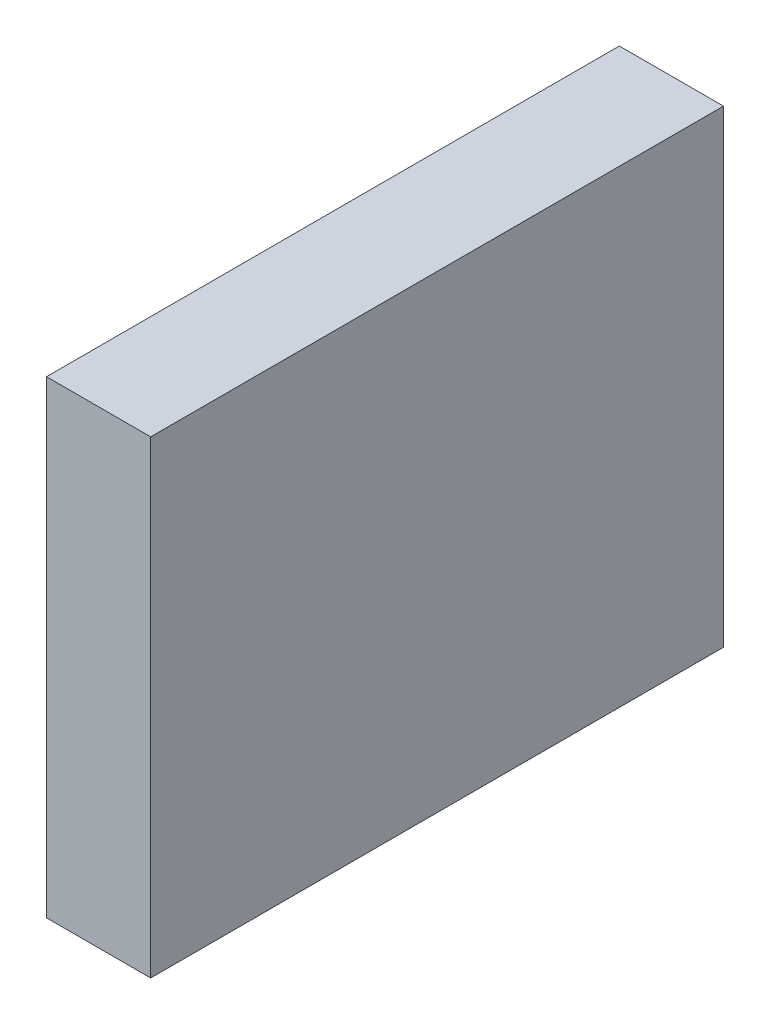
SolidWorks part; units mm, degrees
ref_plane "前视基准面" through (0, 0, 0) normal (0, 0, 1) x (1, 0, 0)
ref_plane "上视基准面" through (0, 0, 0) normal (0, 1, 0) x (1, 0, 0)
ref_plane "右视基准面" through (0, 0, 0) normal (1, 0, 0) x (0, 0, -1)
other "Configuration Table"
sketch "草图1" plane through (0, 0, 0) normal (0, 0, 1) x (1, 0, 0)
  line L0 (0, 0) -> (4, 0)
  line L1 (4, 0) -> (4, 18)
  line L2 (4, 18) -> (0, 18)
  line L3 (0, 18) -> (0, 0)
  dimension "width" = 4
  dimension "height" = 18
extrude "Pitch_Yoke_Arm" add sketch "草图1" along normal blind 22
